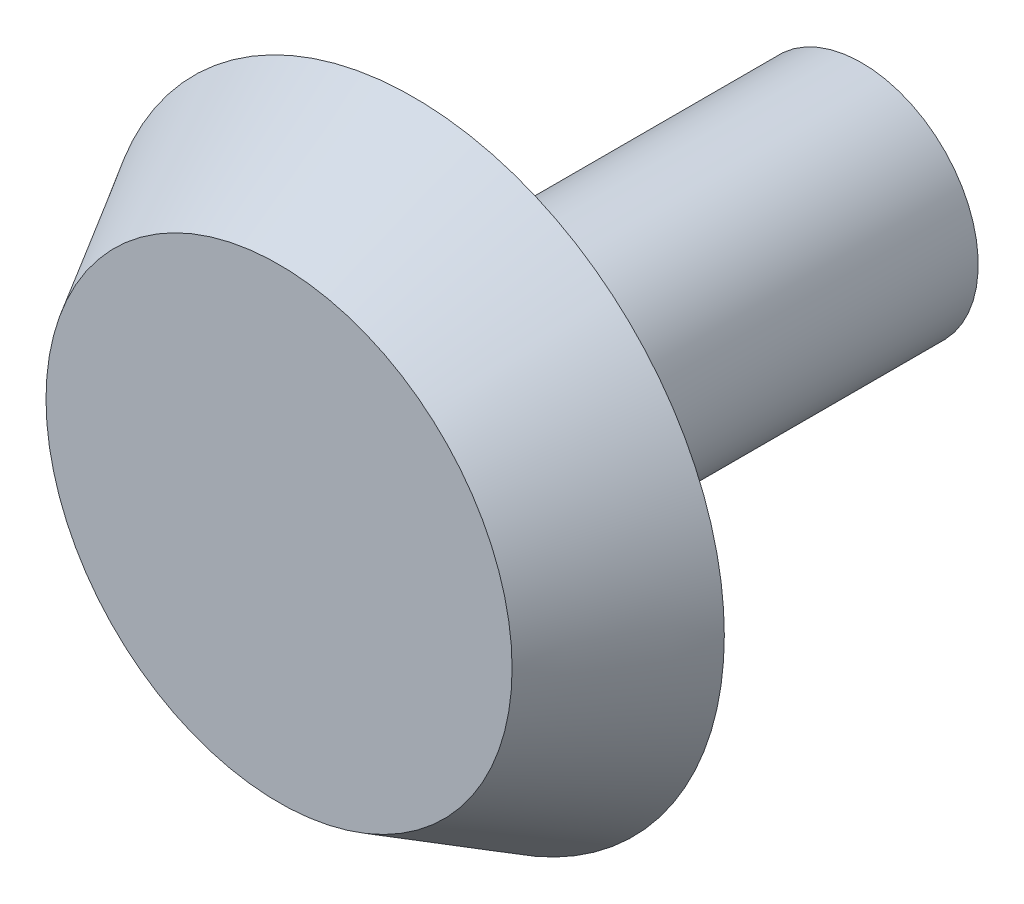
SolidWorks part; units mm, degrees
ref_plane "Front Plane" through (0, 0, 0) normal (0, 0, 1) x (1, 0, 0)
ref_plane "Top Plane" through (0, 0, 0) normal (0, 1, 0) x (1, 0, 0)
ref_plane "Right Plane" through (0, 0, 0) normal (1, 0, 0) x (0, 0, -1)
sketch "Sketch1" plane through (0, 0, 0) normal (0, 1, 0) x (1, 0, 0)
  line L0 (0, 93.4105) -> (0, -92.505) construction
  line L1 (-75.7545, 0) -> (85.7143, 0) construction
  line L2 (0, 75) -> (15, 75)
  line L3 (15, 75) -> (15, 10)
  line L4 (15, 10) -> (30, 10)
  line L5 (30, 10) -> (40, 17.3205)
  line L6 (40, 17.3205) -> (30, 0)
  line L7 (30, 0) -> (0, 0)
  line L8 (0, 75) -> (0, 0)
  dimension "D1" = 75
  dimension "D2" = 15
  dimension "D3" = 30
  dimension "D4" = 10
  dimension "D5" = 60
  dimension "D6" = 40
  dimension "D7" = 30
revolve "Revolve1" add sketch "Sketch1" angle 360 about L8
